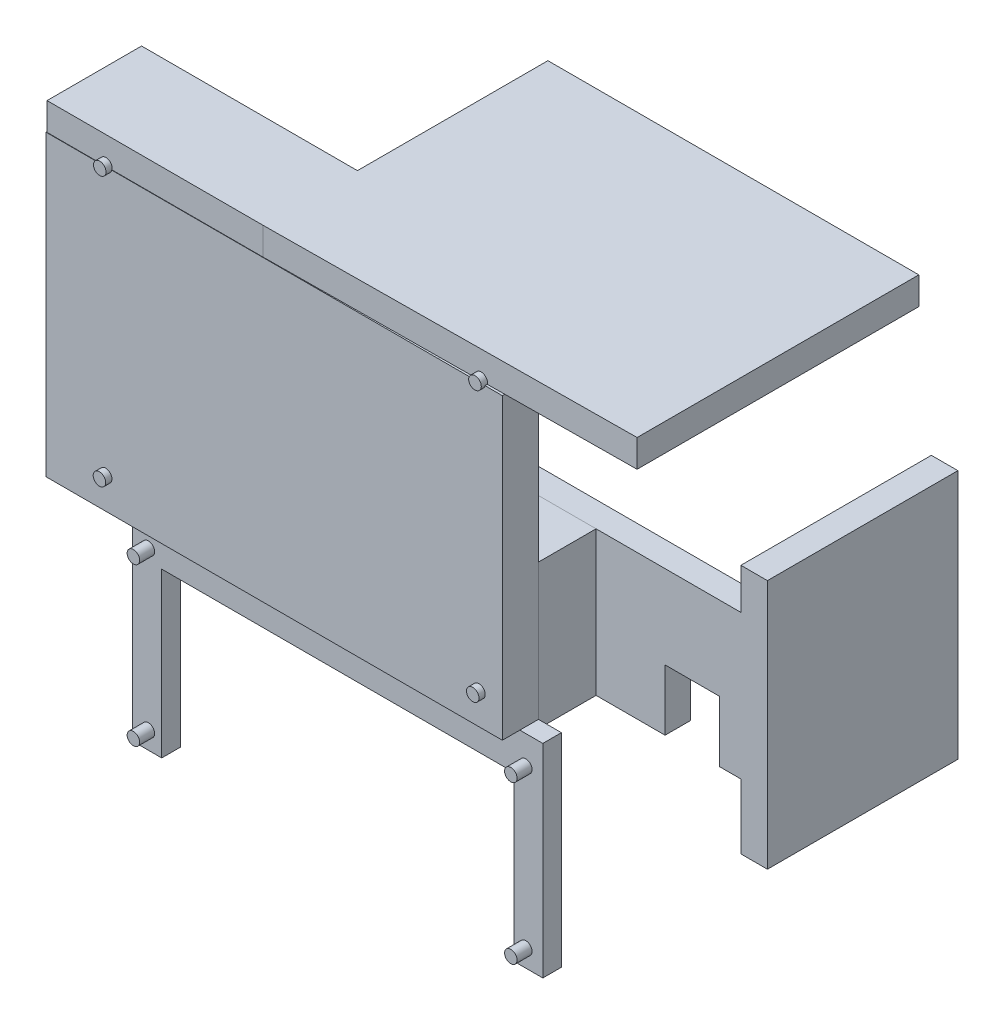
SolidWorks part; units mm, degrees
ref_plane "Front Plane" through (0, 0, 0) normal (0, 0, 1) x (1, 0, 0)
ref_plane "Top Plane" through (0, 0, 0) normal (0, 1, 0) x (1, 0, 0)
ref_plane "Right Plane" through (0, 0, 0) normal (1, 0, 0) x (0, 0, -1)
sketch "Sketch2" plane through (0, 0, 1338.3738) normal (0, 0, 1) x (1, 0, 0)
  line L0 (467.6586, 915.761) -> (541.8597, 915.761) construction
  line L1 (467.6586, 921.2704) -> (541.8597, 921.2704)
  line L2 (467.6586, 921.2704) -> (467.6586, 915.761)
  line L3 (467.6586, 915.761) -> (541.8597, 915.761)
  line L4 (541.8597, 921.2704) -> (541.8597, 915.761)
  line L6 (549.6694, 891.2549) -> (544.3624, 891.2549)
  line L7 (549.6694, 891.2549) -> (549.6694, 841.2516)
  line L8 (549.6694, 841.2516) -> (544.3624, 841.2516)
  line L9 (544.3624, 891.2549) -> (544.3624, 841.2516)
extrude "Boss-Extrude1" add sketch "Sketch2" along normal blind 31.75
sketch "Sketch3" plane through (0, 0, 1338.3738) normal (0, 0, -1) x (-1, 0, 0)
  line L1 (-467.6586, 921.2704) -> (-541.8597, 921.2704)
  line L2 (-467.6586, 921.2704) -> (-467.6586, 915.761)
  line L3 (-467.6586, 915.761) -> (-541.8597, 915.761)
  line L4 (-541.8597, 921.2704) -> (-541.8597, 915.761)
  line L5 (-549.6694, 891.2549) -> (-544.3624, 891.2549)
  line L6 (-549.6694, 891.2549) -> (-549.6694, 841.2516)
  line L7 (-549.6694, 841.2516) -> (-544.3624, 841.2516)
  line L8 (-544.3624, 891.2549) -> (-544.3624, 841.2516)
extrude "Boss-Extrude2" add sketch "Sketch3" along normal blind 6.35
sketch "Sketch4" plane through (544.3624, 0, 0) normal (-1, 0, 0) x (0, 0, 1)
  line L0 (1370.1238, 891.2549) -> (1370.1238, 841.2516) construction
  line L1 (1370.1238, 883.0948) -> (1365.0723, 883.0948)
  line L2 (1370.1238, 883.0948) -> (1370.1238, 854.2321)
  line L3 (1370.1238, 854.2321) -> (1365.0723, 854.2321)
  line L4 (1365.0723, 883.0948) -> (1365.0723, 854.2321)
extrude "Boss-Extrude3" add sketch "Sketch4" along normal blind 124.46
sketch "Sketch5" plane through (0, 0, 1365.0723) normal (0, 0, -1) x (-1, 0, 0)
  line L0 (-419.9024, 854.2321) -> (-544.3624, 854.2321) construction
  line L1 (-419.9024, 883.0948) -> (-424.9036, 883.0948)
  line L2 (-419.9024, 883.0948) -> (-419.9024, 854.2321)
  line L3 (-419.9024, 854.2321) -> (-424.9036, 854.2321)
  line L4 (-424.9036, 883.0948) -> (-424.9036, 854.2321)
  line L5 (-424.9036, 908.1672) -> (-424.9036, 830.3671) construction
extrude "Boss-Extrude4" add sketch "Sketch5" along normal blind 26.67
sketch "Sketch9" plane through (0, 0, 1370.1238) normal (0, 0, 1) x (1, 0, 0)
  line L1 (541.8597, 921.2704) -> (467.6586, 921.2704)
  line L2 (541.8597, 921.2704) -> (541.8597, 915.761)
  line L3 (541.8597, 915.761) -> (467.6586, 915.761)
  line L4 (467.6586, 921.2704) -> (467.6586, 915.761)
extrude "Boss-Extrude7" add sketch "Sketch9" along direction (0, 0, 1) on the side of the normal up to surface (18.2592 mm away) separate body
sketch "Sketch11" plane through (0, 915.761, 0) normal (0, -1, 0) x (1, 0, 0)
  line L1 (424.367, 1389.1055) -> (544.1361, 1389.1055)
  line L2 (424.367, 1389.1055) -> (424.367, 1381.8844)
  line L3 (424.367, 1381.8844) -> (544.1361, 1381.8844)
  line L4 (544.1361, 1389.1055) -> (544.1361, 1381.8844)
extrude "Boss-Extrude8" add sketch "Sketch11" along normal blind 59.69
sketch "Sketch12" plane through (467.6586, 0, 0) normal (-1, 0, 0) x (0, 0, 1)
  line L1 (1389.0306, 921.2704) -> (1370.1238, 921.2704)
  line L2 (1389.0306, 921.2704) -> (1389.0306, 915.761)
  line L3 (1389.0306, 915.761) -> (1370.1238, 915.761)
  line L4 (1370.1238, 921.2704) -> (1370.1238, 915.761)
extrude "Boss-Extrude9" add sketch "Sketch12" along normal blind 43.18
sketch "Sketch13" plane through (0, 0, 1389.1055) normal (0, 0, 1) x (1, 0, 0)
  circle A0 centre (436.2836, 862.2794) radius 1.25
  circle A1 centre (510.9527, 862.2794) radius 1.25
extrude "Boss-Extrude10" add sketch "Sketch13" along normal blind 1.25
sketch "Sketch14" plane through (0, 0, 1389.0306) normal (0, 0, 1) x (1, 0, 0)
  circle A1 centre (436.2695, 916.0494) radius 1.25
extrude "Boss-Extrude11" add sketch "Sketch14" along normal blind 1.25
sketch "Sketch15" plane through (12.1566, 0, 1393.0057) normal (0.0087, 0, 1) x (1, 0, -0.0087)
  circle A0 centre (498.8011, 916.0494) radius 1.25
extrude "Boss-Extrude12" add sketch "Sketch15" along normal blind 1.25
sketch "Sketch17" plane through (0, 0, 1389.1055) normal (0, 0, 1) x (1, 0, 0)
  line L0 (544.1361, 915.761) -> (512.1589, 915.761) construction
  line L1 (515.6277, 915.761) -> (544.1361, 915.761)
  line L2 (515.6277, 915.761) -> (515.6277, 856.071)
  line L3 (515.6277, 856.071) -> (544.1361, 856.071)
  line L4 (544.1361, 915.761) -> (544.1361, 856.071)
extrude "Cut-Extrude1" cut sketch "Sketch17" against normal blind 7.62
sketch "Sketch18" plane through (0, 0, 1370.1238) normal (0, 0, 1) x (1, 0, 0)
  line L0 (419.9024, 854.2321) -> (544.3624, 854.2321) construction
  line L1 (540.1305, 866.4191) -> (529.1976, 866.4191)
  line L2 (540.1305, 866.4191) -> (540.1305, 854.2321)
  line L3 (540.1305, 854.2321) -> (529.1976, 854.2321)
  line L4 (529.1976, 866.4191) -> (529.1976, 854.2321)
extrude "Cut-Extrude2" cut sketch "Sketch18" against normal blind 7.62
sketch "Sketch20" plane through (0, 856.071, 0) normal (0, -1, 0) x (1, 0, 0)
  line L1 (515.6277, 1385.605) -> (520.2244, 1385.605)
  line L2 (515.6277, 1381.8844) -> (438.144, 1381.8844)
  line L4 (515.6277, 1385.605) -> (438.144, 1385.605)
  line L5 (438.144, 1381.8844) -> (438.144, 1385.605)
  line L7 (515.6277, 1381.8844) -> (520.2244, 1381.8844)
  line L8 (520.2244, 1385.605) -> (520.2244, 1381.8844)
extrude "Boss-Extrude13" add sketch "Sketch20" along normal blind 40.64 contours L2 L5 L4 L1 L8 L7
sketch "Sketch21" plane through (0, 0, 1385.605) normal (0, 0, 1) x (1, 0, 0)
  line L0 (438.144, 815.431) -> (520.2244, 815.431) construction
  line L1 (443.994, 848.1502) -> (514.4868, 848.1502)
  line L2 (443.994, 848.1502) -> (443.994, 815.431)
  line L3 (443.994, 815.431) -> (514.4868, 815.431)
  line L4 (514.4868, 848.1502) -> (514.4868, 815.431)
extrude "Cut-Extrude3" cut sketch "Sketch21" against normal blind 12.7
sketch "Sketch22" plane through (0, 0, 1385.605) normal (0, 0, 1) x (1, 0, 0)
  circle A0 centre (516.8244, 850.4537) radius 1.25
  circle A1 centre (516.8244, 818.9537) radius 1.25
  circle A2 centre (441.3244, 850.4537) radius 1.25
  circle A3 centre (441.3244, 818.9537) radius 1.25
extrude "Boss-Extrude14" add sketch "Sketch22" along normal blind 3
sketch "Sketch24" plane through (0, 0, 1381.8844) normal (0, 0, -1) x (-1, 0, 0)
  line L0 (-424.9036, 883.0948) -> (-544.3624, 883.0948) construction
  line L1 (-425.9821, 882.6582) -> (-461.6727, 882.6582)
  line L2 (-425.9821, 882.6582) -> (-425.9821, 853.7462)
  line L3 (-425.9821, 853.7462) -> (-461.6727, 853.7462)
  line L4 (-461.6727, 882.6582) -> (-461.6727, 853.7462)
  line L5 (-515.399, 883.0948) -> (-478.1252, 883.0948)
  line L6 (-515.399, 883.0948) -> (-515.399, 854.2321)
  line L7 (-515.399, 854.2321) -> (-478.1252, 854.2321)
  line L8 (-478.1252, 883.0948) -> (-478.1252, 854.2321)
  line L9 (-424.9036, 854.2321) -> (-529.1976, 854.2321) construction
extrude "Boss-Extrude15" add sketch "Sketch24" along normal up to next separate body contours L2 L1 L4 L3 | L6 L5 L8 L7
sketch "Sketch25" plane through (0, 0, 1381.8844) normal (0, 0, -1) x (-1, 0, 0)
  line L0 (-424.9036, 883.0948) -> (-544.3624, 883.0948) construction
  line L1 (-427.8646, 883.0948) -> (-459.2353, 883.0948)
  line L2 (-427.8646, 883.0948) -> (-427.8646, 854.2321)
  line L3 (-427.8646, 854.2321) -> (-459.2353, 854.2321)
  line L4 (-459.2353, 883.0948) -> (-459.2353, 854.2321)
  line L5 (-424.9036, 854.2321) -> (-529.1976, 854.2321) construction
extrude "Boss-Extrude16" add sketch "Sketch25" along normal up to next
